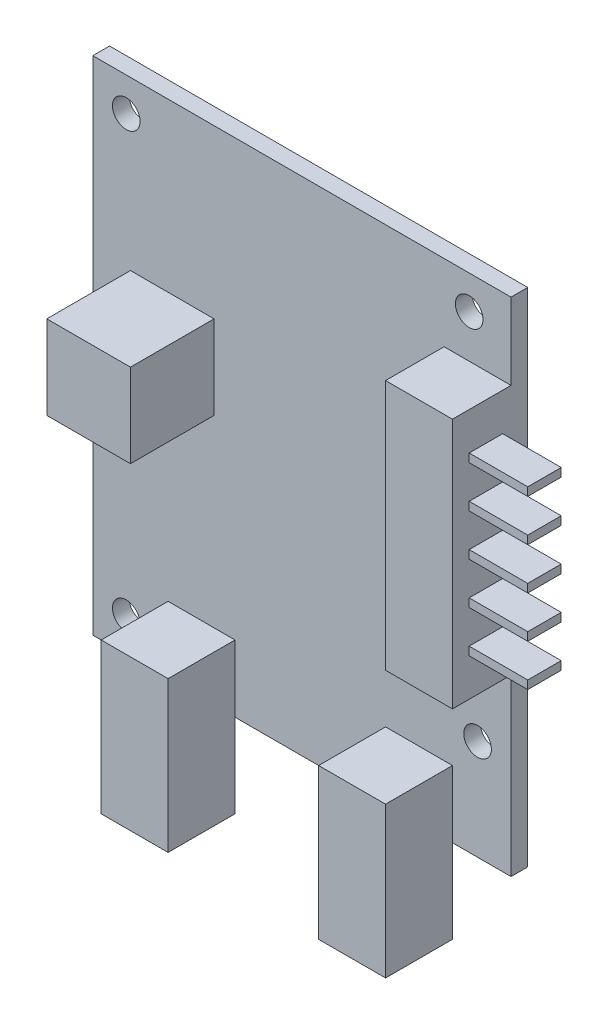
SolidWorks part; units mm, degrees
ref_plane "Plan de face" through (0, 0, 0) normal (0, 0, 1) x (1, 0, 0)
ref_plane "Plan de dessus" through (0, 0, 0) normal (0, 1, 0) x (1, 0, 0)
ref_plane "Plan de droite" through (0, 0, 0) normal (1, 0, 0) x (0, 0, -1)
sketch "Esquisse1" plane through (0, 0, 0) normal (0, 0, 1) x (1, 0, 0)
  line L0 (-23.5099, 59.8027) -> (26.4901, 59.8027)
  line L1 (-23.5099, 59.8027) -> (-23.5099, -0.1973)
  line L2 (-23.5099, -0.1973) -> (26.4901, -0.1973)
  line L3 (26.4901, 59.8027) -> (26.4901, -0.1973)
  circle A0 centre (-19.5099, 55.8027) radius 1.65
  circle A1 centre (21.4901, 55.8027) radius 1.65
  circle A2 centre (22.4901, 11.8027) radius 1.65
  circle A3 centre (-19.5099, 3.8027) radius 1.65
  dimension "D3" = 3.3
  dimension "D1" = 50
  dimension "D2" = 60
  dimension "D4" = 4
  dimension "D5" = 52
  dimension "D6" = 5
  dimension "D7" = 41
  dimension "D8" = 44
  dimension "D9" = 4
extrude "Boss.-Extru.1" add sketch "Esquisse1" along normal blind 2
sketch "Esquisse2" plane through (0, 0, 2) normal (0, 0, 1) x (1, 0, 0)
  line L0 (-23.5099, -0.1973) -> (26.4901, -0.1973) construction
  line L1 (-14.5099, 7.8027) -> (-6.5099, 7.8027)
  line L2 (-14.5099, 7.8027) -> (-14.5099, -10.1973)
  line L3 (-14.5099, -10.1973) -> (-6.5099, -10.1973)
  line L4 (-6.5099, 7.8027) -> (-6.5099, -10.1973)
  line L5 (11.4901, 7.8027) -> (19.4901, 7.8027)
  line L6 (11.4901, 7.8027) -> (11.4901, -10.1973)
  line L7 (11.4901, -10.1973) -> (19.4901, -10.1973)
  line L8 (19.4901, 7.8027) -> (19.4901, -10.1973)
  point P10 (1.4901, -0.1973)
  point P11 (-10.5099, -10.1973)
  point P12 (15.4901, -10.1973)
  dimension "D1" = 8
  dimension "D2" = 8
  dimension "D3" = 10
  dimension "D4" = 12
  dimension "D5" = 14
extrude "Boss.-Extru.2" add sketch "Esquisse2" along normal blind 8
sketch "Esquisse3" plane through (0, 0, 2) normal (0, 0, 1) x (1, 0, 0)
  line L0 (-19.0099, 39.8027) -> (-9.0099, 39.8027)
  line L1 (-19.0099, 39.8027) -> (-19.0099, 29.8027)
  line L2 (-19.0099, 29.8027) -> (-9.0099, 29.8027)
  line L3 (-9.0099, 39.8027) -> (-9.0099, 29.8027)
  line L4 (-23.5099, 59.8027) -> (-23.5099, -0.1973) construction
  line L5 (26.4901, 59.8027) -> (-23.5099, 59.8027) construction
  dimension "D1" = 4.5
  dimension "D2" = 20
  dimension "D3" = 10
extrude "Boss.-Extru.3" add sketch "Esquisse3" along normal blind 10
sketch "Esquisse4" plane through (0, 0, 2) normal (0, 0, 1) x (1, 0, 0)
  line L0 (26.4901, -0.1973) -> (26.4901, 59.8027) construction
  line L1 (18.4901, 50.6627) -> (26.4901, 50.6627)
  line L2 (18.4901, 50.6627) -> (18.4901, 20.6627)
  line L3 (18.4901, 20.6627) -> (26.4901, 20.6627)
  line L4 (26.4901, 50.6627) -> (26.4901, 20.6627)
  line L5 (26.4901, 59.8027) -> (-23.5099, 59.8027) construction
  point P8 (26.4901, 35.6627)
  dimension "D1" = 8
  dimension "D2" = 30
  dimension "D3" = 24.14
extrude "Boss.-Extru.4" add sketch "Esquisse4" along normal blind 7
sketch "Esquisse5" plane through (26.4901, 0, 0) normal (1, 0, 0) x (0, 0, -1)
  line L0 (0, -0.1973) -> (0, 59.8027) construction
  line L1 (-7, 35.1627) -> (-3, 35.1627)
  line L2 (-7, 35.1627) -> (-7, 36.1627)
  line L3 (-7, 36.1627) -> (-3, 36.1627)
  line L4 (-3, 35.1627) -> (-3, 36.1627)
  line L5 (-9, 20.6627) -> (-9, 50.6627) construction
  line L14 (-7, 35.1627) -> (-7, 36.1627)
  line L15 (-7, 35.1627) -> (-3, 35.1627)
  line L16 (-3, 35.1627) -> (-3, 36.1627)
  line L17 (-7, 36.1627) -> (-3, 36.1627)
  line L26 (-7, 35.1627) -> (-7, 36.1627)
  line L27 (-7, 35.1627) -> (-3, 35.1627)
  line L28 (-3, 35.1627) -> (-3, 36.1627)
  line L29 (-7, 36.1627) -> (-3, 36.1627)
  line L38 (-7, 40.1627) -> (-7, 41.1627)
  line L39 (-7, 40.1627) -> (-3, 40.1627)
  line L40 (-3, 40.1627) -> (-3, 41.1627)
  line L41 (-7, 41.1627) -> (-3, 41.1627)
  line L42 (-7, 45.1627) -> (-7, 46.1627)
  line L43 (-7, 45.1627) -> (-3, 45.1627)
  line L44 (-3, 45.1627) -> (-3, 46.1627)
  line L45 (-7, 46.1627) -> (-3, 46.1627)
  line L46 (-7, 30.1627) -> (-7, 31.1627)
  line L47 (-7, 30.1627) -> (-3, 30.1627)
  line L48 (-3, 30.1627) -> (-3, 31.1627)
  line L49 (-7, 31.1627) -> (-3, 31.1627)
  line L50 (-7, 25.1627) -> (-7, 26.1627)
  line L51 (-7, 25.1627) -> (-3, 25.1627)
  line L52 (-3, 25.1627) -> (-3, 26.1627)
  line L53 (-7, 26.1627) -> (-3, 26.1627)
  point P8 (-9, 35.6627)
  point P9 (-7, 35.6627)
  dimension "D1" = 1
  dimension "D2" = 4
  dimension "D3" = 7
  dimension "D4" = 3
  dimension "D5" = 3
extrude "Boss.-Extru.5" add sketch "Esquisse5" along normal blind 7 contours L2 L1 L4 L3 | L46 L49 L48 L47 | L50 L53 L52 L51 | L38 L41 L40 L39 | L42 L45 L44 L43
